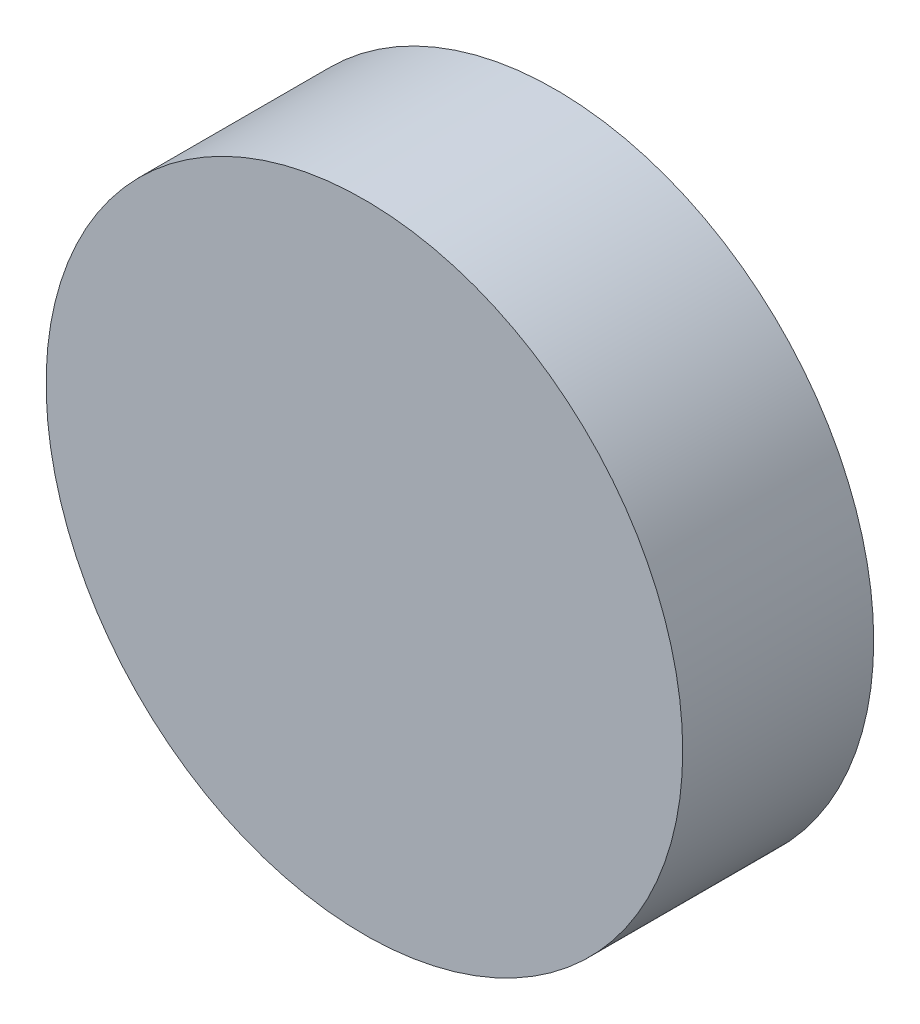
SolidWorks part; units mm, degrees
ref_plane "Piano frontale" through (0, 0, 0) normal (0, 0, 1) x (1, 0, 0)
ref_plane "Piano superiore" through (0, 0, 0) normal (0, 1, 0) x (1, 0, 0)
ref_plane "Piano destro" through (0, 0, 0) normal (1, 0, 0) x (0, 0, -1)
sketch "Schizzo1" plane through (0, 0, 0) normal (0, 0, 1) x (1, 0, 0)
  circle A0 centre (26.25, -62.1867) radius 5
  dimension "D1" = 10
extrude "Estrusione-Estrusione1" add sketch "Schizzo1" along normal blind 3
